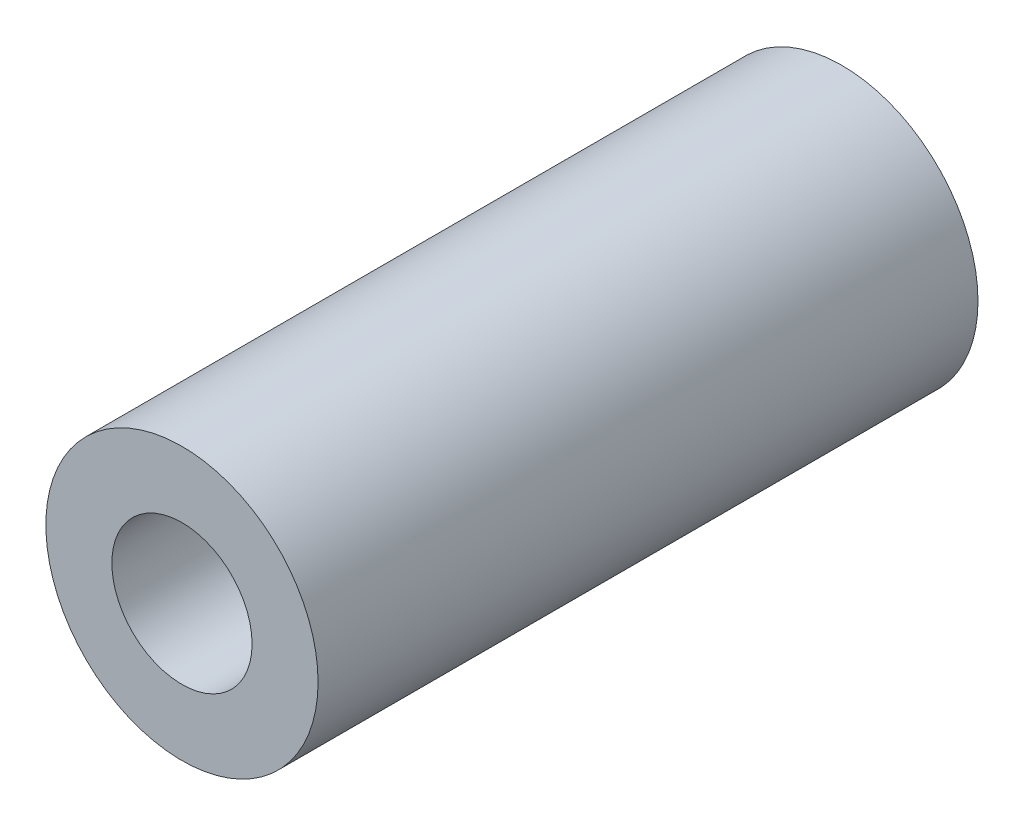
SolidWorks part; units mm, degrees
ref_plane "Front Plane" through (0, 0, 0) normal (0, 0, 1) x (1, 0, 0)
ref_plane "Top Plane" through (0, 0, 0) normal (0, 1, 0) x (1, 0, 0)
ref_plane "Right Plane" through (0, 0, 0) normal (1, 0, 0) x (0, 0, -1)
sketch "Sketch1" plane through (0, 0, 0) normal (0, 0, 1) x (1, 0, 0)
  circle A0 centre (0, 0) radius 3.3
  circle A1 centre (0, 0) radius 1.7
  dimension "D1" = 6.6
  dimension "D2" = 3.4
extrude "Boss-Extrude1" add sketch "Sketch1" along normal blind 16
